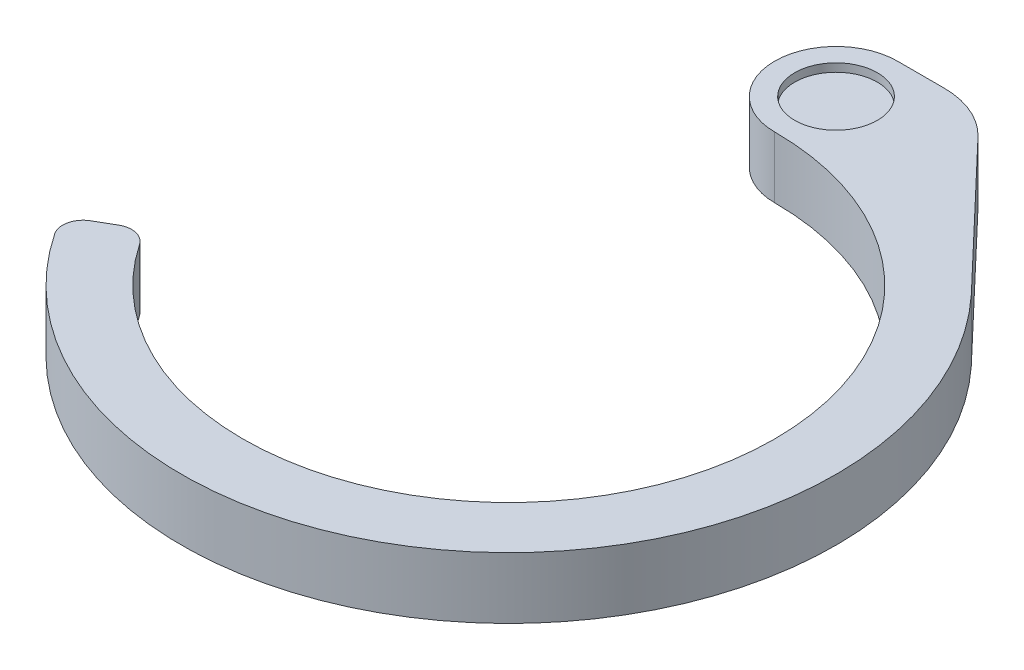
SolidWorks part; units mm, degrees
ref_plane "正面" through (0, 0, 0) normal (0, 0, 1) x (1, 0, 0)
ref_plane "平面" through (0, 0, 0) normal (0, 1, 0) x (1, 0, 0)
ref_plane "右側面" through (0, 0, 0) normal (1, 0, 0) x (0, 0, -1)
sketch "ｽｹｯﾁ2" plane through (0, 0, 0) normal (0, 1, 0) x (1, 0, 0)
  line L1 (-1.8089, 2.6033) -> (0, 0)
  line L2 (-60.4669, -34.9106) -> (-64.8074, -37.4166)
  line L4 (0, 95) -> (11.4274, 95)
  line L5 (25.9115, 88.7917) -> (58.5757, 54.4875)
  arc A0 (-66.4612, -44.5298) -> (57.2894, 55.8384) centre (0, 0) ccw
  arc A1 (-53.8264, -36.4378) -> (0, 65) centre (0, 0) ccw
  arc A2 (0, 95) -> (0, 65) centre (0, 80) ccw
  arc A3 (11.4274, 95) -> (25.9115, 88.7917) centre (11.4274, 75) cw
  arc A4 (-53.8264, -36.4378) -> (-60.4669, -34.9106) centre (-57.9669, -39.2407) ccw
  arc A5 (-66.4612, -44.5298) -> (-64.8074, -37.4166) centre (-62.3074, -41.7467) cw
  dimension "D1" = 160
  dimension "D2" = 130
  dimension "D4" = 20
  dimension "D5" = 5
  dimension "D6" = 5
extrude "ﾎﾞｽ - 押し出し4" add sketch "ｽｹｯﾁ2" along normal blind 15 contours A5 A0 L5 A3 L4 A2 A1 A4 L2
sketch "ｽｹｯﾁ3" plane through (0, 15, 0) normal (0, 1, 0) x (1, 0, 0)
  circle A0 centre (0, 80) radius 10.1
  dimension "D1" = 20.2
extrude "ｶｯﾄ - 押し出し1" cut sketch "ｽｹｯﾁ3" against normal blind 2
